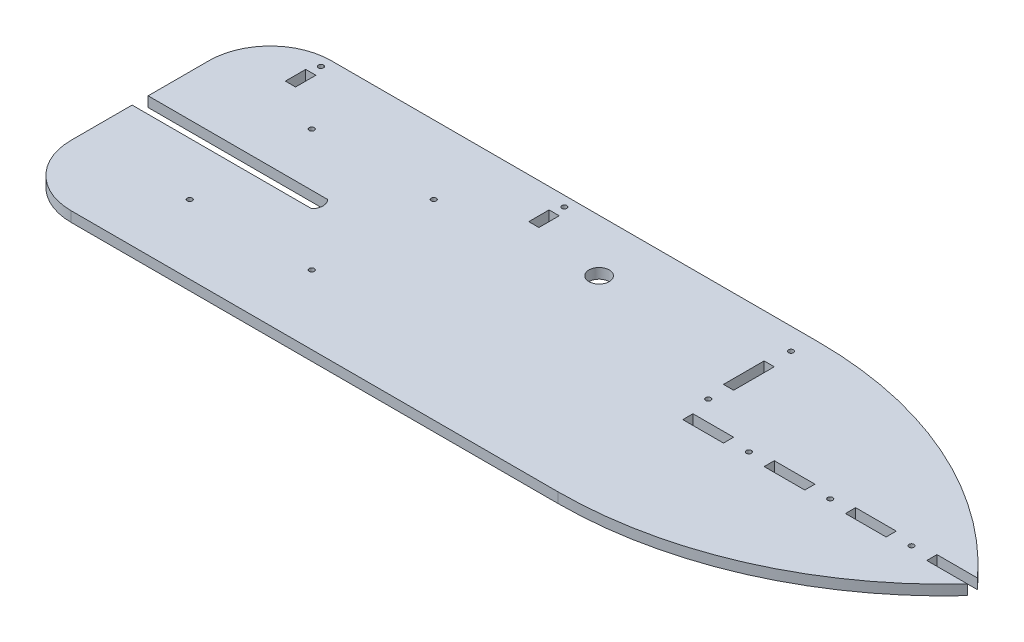
SolidWorks part; units mm, degrees
material "6061 Alloy"
ref_plane "Front Plane" through (0, 0, 0) normal (0, 0, 1) x (1, 0, 0)
ref_plane "Top Plane" through (0, 0, 0) normal (0, 1, 0) x (1, 0, 0)
ref_plane "Right Plane" through (0, 0, 0) normal (1, 0, 0) x (0, 0, -1)
sketch "Sketch1" plane through (0, 0, 0) normal (0, 1, 0) x (1, 0, 0)
  line L0 (-158.3722, 3.8742) -> (-259.9722, 3.8742)
  line L1 (-158.3722, -6.1334) -> (-259.9722, -6.1334)
  line L2 (-259.9722, -6.1334) -> (-259.9722, -44.2334)
  line L3 (-259.9722, 3.8742) -> (-259.9722, 41.9742)
  line L4 (-221.8722, 80.0742) -> (82.1722, 80.0742)
  line L5 (-221.8722, -82.3334) -> (82.1722, -82.3334)
  line L6 (82.1722, 2.0454) -> (82.1722, -4.3046)
  line L7 (82.1722, -4.3046) -> (107.5722, -4.3046)
  line L8 (107.5722, -4.3046) -> (107.5722, 2.0454)
  line L9 (107.5722, 2.0454) -> (82.1722, 2.0454)
  line L10 (132.9722, 2.0454) -> (158.3722, 2.0454)
  line L11 (158.3722, 2.0454) -> (158.3722, -4.3046)
  line L12 (132.9722, 2.0454) -> (132.9722, -4.3046)
  line L13 (132.9722, -4.3046) -> (158.3722, -4.3046)
  line L14 (209.1722, 2.0454) -> (183.7722, 2.0454)
  line L15 (183.7722, 2.0454) -> (183.7722, -4.3046)
  line L16 (183.7722, -4.3046) -> (209.1722, -4.3046)
  line L17 (209.1722, -4.3046) -> (209.1722, 2.0454)
  line L18 (259.9722, 2.0454) -> (234.5722, 2.0454)
  line L19 (234.5722, 2.0454) -> (234.5722, -4.3046)
  line L20 (234.5722, -4.3046) -> (259.9722, -4.3046)
  line L21 (75.8222, 27.4454) -> (82.1722, 27.4454)
  line L22 (75.8222, 27.4454) -> (75.8222, 52.8454)
  line L23 (75.8222, 52.8454) -> (82.1722, 52.8454)
  line L24 (82.1722, 52.8454) -> (82.1722, 27.4454)
  line L25 (-221.8722, 67.3742) -> (-218.6972, 67.3742)
  line L26 (-218.6972, 67.3742) -> (-218.6972, 54.6742)
  line L27 (-218.6972, 54.6742) -> (-225.0472, 54.6742)
  line L28 (-225.0472, 54.6742) -> (-225.0472, 67.3742)
  line L29 (-225.0472, 67.3742) -> (-221.8722, 67.3742)
  line L30 (-69.85, 67.3742) -> (-66.675, 67.3742)
  line L31 (-66.675, 67.3742) -> (-66.675, 54.6742)
  line L32 (-66.675, 54.6742) -> (-73.025, 54.6742)
  line L33 (-73.025, 54.6742) -> (-73.025, 67.3742)
  line L34 (-73.025, 67.3742) -> (-69.85, 67.3742)
  line L35 (-147.8827, 3.8742) -> (-158.3722, 3.8742)
  line L36 (-147.8827, -6.1334) -> (-158.3722, -6.1334)
  arc A0 (-259.9722, -44.2334) -> (-221.8722, -82.3334) centre (-221.8722, -44.2334) ccw
  arc A1 (-221.8722, 80.0742) -> (-259.9722, 41.9742) centre (-221.8722, 41.9742) ccw
  circle A2 centre (-190.8778, -39.2296) radius 1.5875
  circle A3 centre (-114.6778, -39.2296) radius 1.5875
  circle A4 centre (-114.6778, 36.9704) radius 1.5875
  circle A5 centre (-190.8778, 36.9704) radius 1.5875
  circle A6 centre (120.2722, -1.1296) radius 1.5875
  circle A7 centre (171.0722, -1.1296) radius 1.5875
  circle A8 centre (221.8722, -1.1296) radius 1.5875
  arc A9 (259.9722, 2.0454) -> (82.1722, 80.0742) centre (82.1722, -161.5118) ccw
  arc A10 (82.1722, -82.3334) -> (259.9722, -4.3046) centre (82.1722, 159.2526) ccw
  circle A11 centre (78.9972, 14.7454) radius 1.5875
  circle A12 centre (78.9972, 66.4598) radius 1.5875
  circle A13 centre (-21.7664, 47.3688) radius 6.35
  circle A14 centre (-221.8722, 73.7242) radius 1.5875
  circle A15 centre (-69.85, 73.7242) radius 1.5875
  arc A16 (-147.8827, -6.1334) -> (-147.8827, 3.8742) centre (-152.7778, -1.1296) ccw
extrude "Boss-Extrude1" add sketch "Sketch1" along normal blind 6.35
